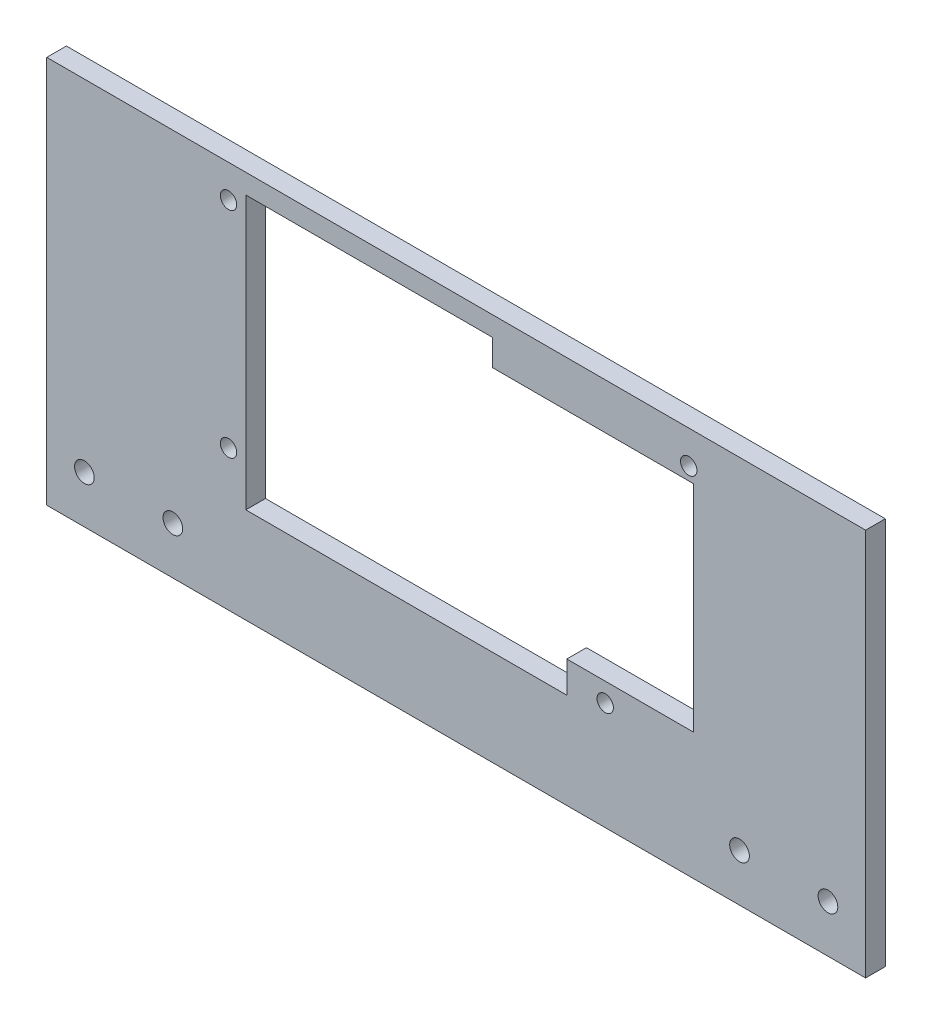
SolidWorks part; units mm, degrees
ref_plane "Plan de face" through (0, 0, 0) normal (0, 0, 1) x (1, 0, 0)
ref_plane "Plan de dessus" through (0, 0, 0) normal (0, 1, 0) x (1, 0, 0)
ref_plane "Plan de droite" through (0, 0, 0) normal (1, 0, 0) x (0, 0, -1)
sketch "Esquisse1" plane through (0, 0, 0) normal (0, 0, 1) x (1, 0, 0)
  line L0 (-50, 6) -> (-50, 0) construction
  line L1 (200, 6) -> (-50, 6)
  line L2 (200, 6) -> (200, -112.4149)
  line L3 (200, -112.4149) -> (-50, -112.4149)
  line L4 (-50, 6) -> (-50, -112.4149)
extrude "Boss.-Extru.1" add sketch "Esquisse1" along normal blind 6
sketch "Esquisse2" plane through (0, 0, 0) normal (0, 0, -1) x (-1, 0, 0)
  line L0 (-10.7824, 0) -> (-10.7824, -83.25)
  line L1 (-200, 0) -> (50, 0) construction
  line L2 (-10.7824, -83.25) -> (-108.7787, -83.25)
  line L3 (-108.7787, -83.25) -> (-108.7787, -73.6819)
  line L4 (-108.7787, -73.6819) -> (-147.5, -73.6819)
  line L5 (-147.5, -73.6819) -> (-147.5, -8)
  line L6 (-147.5, -8) -> (-86.1527, -8)
  line L7 (-86.1527, -8) -> (-86.1527, 0)
  line L8 (-86.1527, 0) -> (-10.7824, 0)
  line L9 (-53.0222, -85) -> (-53, -81.5) construction
  line L10 (0, -85) -> (-150, -85) construction
  line L11 (-145, -23.555) -> (-150, -23.555) construction
  line L12 (-145, -35.11) -> (-145, -12) construction
  line L13 (-150, -85) -> (-150, 0) construction
  line L14 (-145, -12) -> (-146, -12) construction
  line L15 (-146, -12) -> (-146, -4) construction
  line L16 (-95, -12) -> (-77.3053, -12) construction
  circle A0 centre (-53, -42.5) radius 39 construction
  point P16 (-53.0111, -83.25)
  point P23 (-147.5, -23.555)
  point P27 (-146, -8)
  point P33 (-86.1527, -12)
extrude "Enlèv. mat.-Extru.1" cut sketch "Esquisse2" against normal up to next
sketch "Esquisse3" plane through (0, 0, 0) normal (0, 0, -1) x (-1, 0, 0)
  circle A0 centre (-5.5, -69.5) radius 2.5
  circle A1 centre (-5.5, -4) radius 2.5
  circle A2 centre (-146, -4) radius 2.5
  circle A3 centre (-120.5, -79.5) radius 2.5
  dimension "D1" = 5
extrude "Enlèv. mat.-Extru.2" cut sketch "Esquisse3" against normal up to next
sketch "Esquisse4" plane through (0, 0, 0) normal (0, 0, -1) x (-1, 0, 0)
  circle A0 centre (-188.5, -97.9149) radius 3
  circle A1 centre (-161.5, -97.9149) radius 3
  dimension "D1" = 6
extrude "Enlèv. mat.-Extru.3" cut sketch "Esquisse4" against normal up to next
ref_plane "Plan1" through (75, 0, 0) normal (1, 0, 0) x (0, 0, -1)
mirror "Symétrie1" about plane through (75, 0, 0) normal (1, 0, 0) of "Enlèv. mat.-Extru.3"
